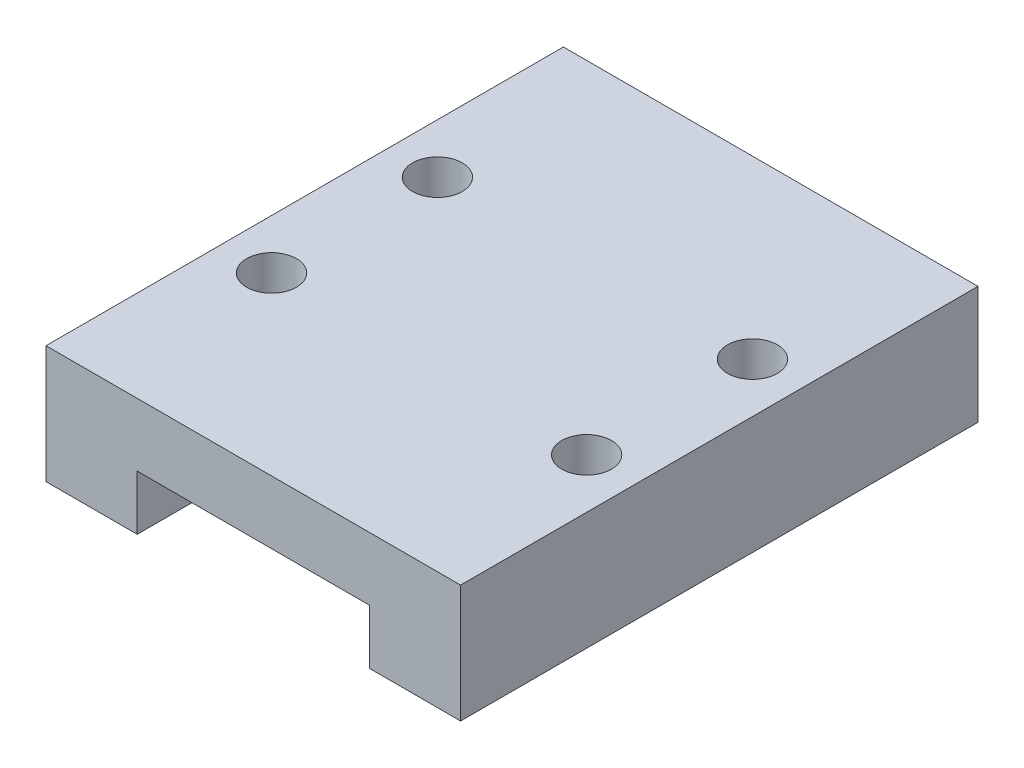
SolidWorks part; units mm, degrees
ref_plane "前视基准面" through (0, 0, 0) normal (0, 0, 1) x (1, 0, 0)
ref_plane "上视基准面" through (0, 0, 0) normal (0, 1, 0) x (1, 0, 0)
ref_plane "右视基准面" through (0, 0, 0) normal (1, 0, 0) x (0, 0, -1)
sketch "草图1" plane through (0, 0, 0) normal (0, 0, 1) x (1, 0, 0)
  line L1 (-12.5, -3.55) -> (12.5, -3.55)
  line L2 (-12.5, -3.55) -> (-12.5, 3.55)
  line L3 (-12.5, 3.55) -> (12.5, 3.55)
  line L4 (12.5, -3.55) -> (12.5, 3.55)
  line L5 (-12.5, -3.55) -> (12.5, 3.55) construction
  line L6 (-12.5, 3.55) -> (12.5, -3.55) construction
  point P0 (0, 0)
  dimension "D1" = 25
  dimension "D2" = 7.1
extrude "凸台-拉伸1" add sketch "草图1" along normal mid plane 31.2
sketch "草图2" plane through (0, 0, 15.6) normal (0, 0, 1) x (1, 0, 0)
  line L0 (-12.5, -3.55) -> (12.5, -3.55) construction
  line L1 (-7, -3.55) -> (7, -3.55)
  line L2 (-7, -3.55) -> (-7, -0.25)
  line L3 (-7, -0.25) -> (7, -0.25)
  line L4 (7, -3.55) -> (7, -0.25)
  dimension "D1" = 7
  dimension "D2" = 14
  dimension "D3" = 3.3
extrude "切除-拉伸1" cut sketch "草图2" against normal through all both and the other way through all
sketch "草图3" plane through (0, 3.55, 0) normal (0, 1, 0) x (1, 0, 0)
  circle A0 centre (9.5, -5) radius 1.5
  circle A1 centre (-9.5, -5) radius 1.5
  circle A2 centre (-9.5, 5) radius 1.5
  circle A3 centre (9.5, 5) radius 1.5
  dimension "D1" = 3
  dimension "D2" = 3
  dimension "D3" = 3
  dimension "D4" = 3
  dimension "D5" = 9.5
  dimension "D6" = 19
  dimension "D7" = 5
  dimension "D8" = 19
  dimension "D9" = 9.5
  dimension "D10" = 5
  dimension "D11" = 5
  dimension "D12" = 5
extrude "切除-拉伸2" cut sketch "草图3" against normal blind 3
